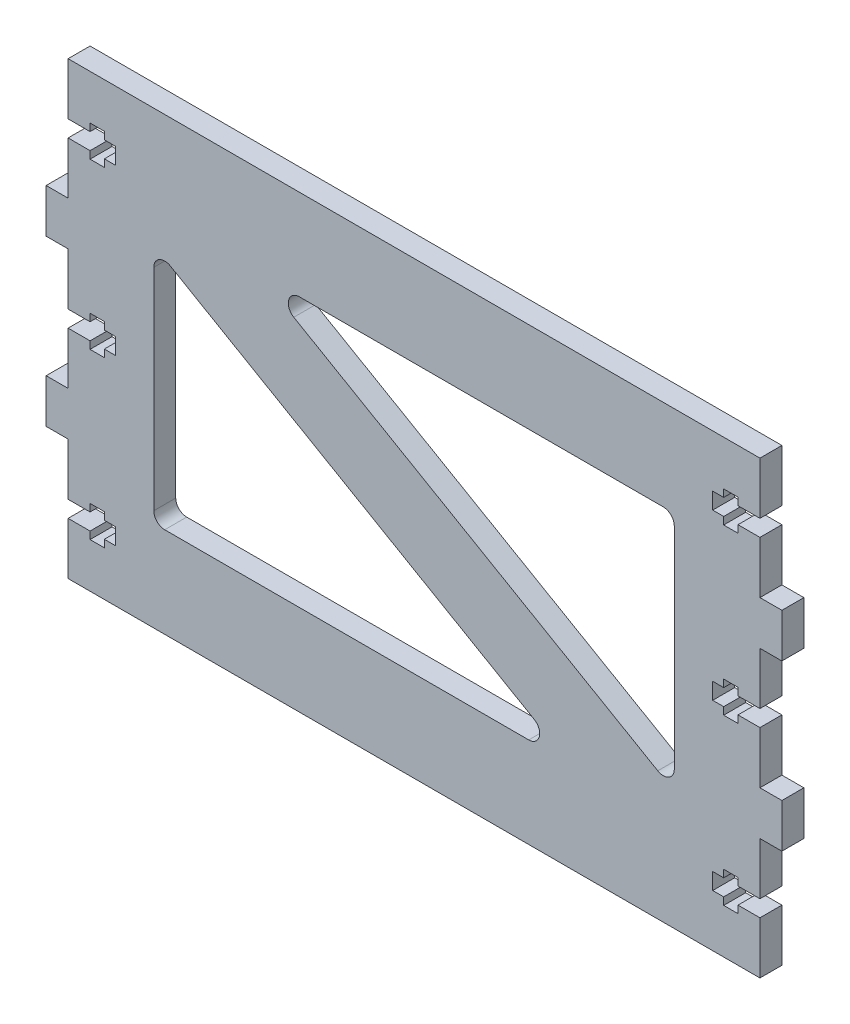
SolidWorks part; units mm, degrees
ref_plane "前视基准面" through (0, 0, 0) normal (0, 0, 1) x (1, 0, 0)
ref_plane "上视基准面" through (0, 0, 0) normal (0, 1, 0) x (1, 0, 0)
ref_plane "右视基准面" through (0, 0, 0) normal (1, 0, 0) x (0, 0, -1)
sketch "草图1" plane through (0, 0, 0) normal (0, 0, 1) x (1, 0, 0)
  line L0 (55.5343, 5.23) -> (-70.4657, 5.23) construction
  line L1 (59.5343, 20.23) -> (57.8313, 20.23) construction
  line L2 (46.9343, -24.77) -> (49.8557, -24.77) construction
  line L3 (59.5343, -9.77) -> (57.8313, -9.77) construction
  line L4 (55.5343, 3.73) -> (55.5343, 6.73) construction
  line L5 (55.5343, 5.23) -> (56.8421, 5.23) construction
  line L6 (55.5343, 6.73) -> (51.5343, 6.73)
  line L7 (51.5343, 6.73) -> (51.5343, 8.08)
  line L8 (51.5343, 8.08) -> (48.9343, 8.08)
  line L9 (48.9343, 8.08) -> (48.9343, 6.73)
  line L10 (48.9343, 6.73) -> (46.9343, 6.73)
  line L11 (48.9343, 2.38) -> (48.9343, 3.73)
  line L12 (51.5343, 3.73) -> (51.5343, 2.38)
  line L13 (48.9343, 3.73) -> (46.9343, 3.73)
  line L14 (51.5343, 2.38) -> (48.9343, 2.38)
  line L15 (55.5343, 3.73) -> (51.5343, 3.73)
  line L16 (55.5343, 24.23) -> (59.5343, 24.23)
  line L17 (59.5343, 24.23) -> (59.5343, 16.23)
  line L18 (59.5343, 16.23) -> (55.5343, 16.23)
  line L19 (55.5343, 16.23) -> (55.5343, 6.73)
  line L20 (-7.4657, 5.23) -> (-7.4657, 11.8034) construction
  line L21 (55.5343, 6.73) -> (51.5343, 6.73)
  line L22 (51.5343, 8.08) -> (48.9343, 8.08)
  line L23 (55.5343, 6.73) -> (51.5343, 6.73)
  line L24 (51.5343, 6.73) -> (51.5343, 8.08)
  line L25 (51.5343, 8.08) -> (48.9343, 8.08)
  line L26 (48.9343, 8.08) -> (48.9343, 6.73)
  line L27 (48.9343, 6.73) -> (46.9343, 6.73)
  line L28 (48.9343, 2.38) -> (48.9343, 3.73)
  line L29 (51.5343, 3.73) -> (51.5343, 2.38)
  line L30 (48.9343, 3.73) -> (46.9343, 3.73)
  line L31 (51.5343, 2.38) -> (48.9343, 2.38)
  line L32 (55.5343, 3.73) -> (51.5343, 3.73)
  line L33 (48.9343, 6.73) -> (46.9343, 6.73)
  line L34 (51.5343, 6.73) -> (51.5343, 8.08)
  line L35 (48.9343, 8.08) -> (48.9343, 6.73)
  line L36 (48.9343, 3.73) -> (46.9343, 3.73)
  line L37 (48.9343, 2.38) -> (48.9343, 3.73)
  line L38 (51.5343, 2.38) -> (48.9343, 2.38)
  line L39 (51.5343, 3.73) -> (51.5343, 2.38)
  line L40 (55.5343, 3.73) -> (51.5343, 3.73)
  line L41 (55.5343, -23.27) -> (55.5343, -13.77)
  line L42 (51.5343, -23.27) -> (55.5343, -23.27)
  line L43 (51.5343, -26.27) -> (55.5343, -26.27)
  line L44 (55.5343, -35.77) -> (55.5343, -26.27)
  line L45 (51.5343, -23.27) -> (51.5343, -21.92)
  line L46 (51.5343, -21.92) -> (48.9343, -21.92)
  line L47 (48.9343, -21.92) -> (48.9343, -23.27)
  line L48 (48.9343, -23.27) -> (46.9343, -23.27)
  line L49 (46.9343, -23.27) -> (46.9343, -26.27)
  line L50 (48.9343, -27.62) -> (48.9343, -26.27)
  line L51 (51.5343, -26.27) -> (51.5343, -27.62)
  line L52 (48.9343, -26.27) -> (46.9343, -26.27)
  line L53 (51.5343, -27.62) -> (48.9343, -27.62)
  line L54 (55.5343, -5.77) -> (55.5343, 3.73)
  line L55 (59.5343, -5.77) -> (55.5343, -5.77)
  line L56 (59.5343, -13.77) -> (59.5343, -5.77)
  line L57 (55.5343, -13.77) -> (59.5343, -13.77)
  line L58 (55.5343, 6.73) -> (51.5343, 6.73)
  line L59 (51.5343, 8.08) -> (48.9343, 8.08)
  line L60 (48.9343, 6.73) -> (46.9343, 6.73)
  line L61 (51.5343, 6.73) -> (51.5343, 8.08)
  line L62 (48.9343, 8.08) -> (48.9343, 6.73)
  line L63 (46.9343, 3.73) -> (46.9343, 6.73)
  line L64 (48.9343, 3.73) -> (46.9343, 3.73)
  line L65 (48.9343, 2.38) -> (48.9343, 3.73)
  line L66 (51.5343, 2.38) -> (48.9343, 2.38)
  line L67 (51.5343, 3.73) -> (51.5343, 2.38)
  line L68 (55.5343, 3.73) -> (51.5343, 3.73)
  line L69 (46.9343, 35.23) -> (49.8557, 35.23) construction
  line L70 (51.5343, 38.08) -> (48.9343, 38.08)
  line L71 (48.9343, 36.73) -> (46.9343, 36.73)
  line L72 (51.5343, 36.73) -> (51.5343, 38.08)
  line L73 (48.9343, 38.08) -> (48.9343, 36.73)
  line L74 (46.9343, 33.73) -> (46.9343, 36.73)
  line L75 (48.9343, 33.73) -> (46.9343, 33.73)
  line L76 (48.9343, 32.38) -> (48.9343, 33.73)
  line L77 (51.5343, 32.38) -> (48.9343, 32.38)
  line L78 (51.5343, 33.73) -> (51.5343, 32.38)
  line L79 (55.5343, 46.23) -> (55.5343, 36.73)
  line L80 (51.5343, 36.73) -> (55.5343, 36.73)
  line L81 (51.5343, 33.73) -> (55.5343, 33.73)
  line L82 (55.5343, 33.73) -> (55.5343, 24.23)
  line L83 (-61.8657, 35.23) -> (-64.7872, 35.23) construction
  line L84 (-70.4657, 5.23) -> (-71.7735, 5.23) construction
  line L85 (-70.4657, 3.73) -> (-70.4657, 6.73) construction
  line L86 (-74.4657, -9.77) -> (-72.7628, -9.77) construction
  line L87 (-61.8657, -24.77) -> (-64.7872, -24.77) construction
  line L88 (-74.4657, 20.23) -> (-72.7628, 20.23) construction
  line L89 (-70.4657, 33.73) -> (-70.4657, 24.23)
  line L90 (-66.4657, 33.73) -> (-70.4657, 33.73)
  line L91 (-66.4657, 36.73) -> (-70.4657, 36.73)
  line L92 (-70.4657, 46.23) -> (-70.4657, 36.73)
  line L93 (-66.4657, 33.73) -> (-66.4657, 32.38)
  line L94 (-66.4657, 32.38) -> (-63.8657, 32.38)
  line L95 (-63.8657, 32.38) -> (-63.8657, 33.73)
  line L96 (-63.8657, 33.73) -> (-61.8657, 33.73)
  line L97 (-61.8657, 33.73) -> (-61.8657, 36.73)
  line L98 (-63.8657, 38.08) -> (-63.8657, 36.73)
  line L99 (-66.4657, 36.73) -> (-66.4657, 38.08)
  line L100 (-63.8657, 36.73) -> (-61.8657, 36.73)
  line L101 (-66.4657, 38.08) -> (-63.8657, 38.08)
  line L102 (-70.4657, 3.73) -> (-66.4657, 3.73)
  line L103 (-66.4657, 3.73) -> (-66.4657, 2.38)
  line L104 (-66.4657, 2.38) -> (-63.8657, 2.38)
  line L105 (-63.8657, 2.38) -> (-63.8657, 3.73)
  line L106 (-63.8657, 3.73) -> (-61.8657, 3.73)
  line L107 (-61.8657, 3.73) -> (-61.8657, 6.73)
  line L108 (-63.8657, 8.08) -> (-63.8657, 6.73)
  line L109 (-66.4657, 6.73) -> (-66.4657, 8.08)
  line L110 (-63.8657, 6.73) -> (-61.8657, 6.73)
  line L111 (-66.4657, 8.08) -> (-63.8657, 8.08)
  line L112 (-70.4657, 6.73) -> (-66.4657, 6.73)
  line L113 (-70.4657, -13.77) -> (-74.4657, -13.77)
  line L114 (-74.4657, -13.77) -> (-74.4657, -5.77)
  line L115 (-74.4657, -5.77) -> (-70.4657, -5.77)
  line L116 (-70.4657, -5.77) -> (-70.4657, 3.73)
  line L117 (-66.4657, -27.62) -> (-63.8657, -27.62)
  line L118 (-63.8657, -26.27) -> (-61.8657, -26.27)
  line L119 (-66.4657, -26.27) -> (-66.4657, -27.62)
  line L120 (-63.8657, -27.62) -> (-63.8657, -26.27)
  line L121 (-61.8657, -23.27) -> (-61.8657, -26.27)
  line L122 (-63.8657, -23.27) -> (-61.8657, -23.27)
  line L123 (-63.8657, -21.92) -> (-63.8657, -23.27)
  line L124 (-66.4657, -21.92) -> (-63.8657, -21.92)
  line L125 (-66.4657, -23.27) -> (-66.4657, -21.92)
  line L126 (-70.4657, -35.77) -> (-70.4657, -26.27)
  line L127 (-66.4657, -26.27) -> (-70.4657, -26.27)
  line L128 (-66.4657, -23.27) -> (-70.4657, -23.27)
  line L129 (-70.4657, -23.27) -> (-70.4657, -13.77)
  line L130 (-70.4657, 3.73) -> (-66.4657, 3.73)
  line L131 (-66.4657, 3.73) -> (-66.4657, 2.38)
  line L132 (-66.4657, 2.38) -> (-63.8657, 2.38)
  line L133 (-63.8657, 2.38) -> (-63.8657, 3.73)
  line L134 (-63.8657, 3.73) -> (-61.8657, 3.73)
  line L135 (-63.8657, 8.08) -> (-63.8657, 6.73)
  line L136 (-66.4657, 6.73) -> (-66.4657, 8.08)
  line L137 (-63.8657, 6.73) -> (-61.8657, 6.73)
  line L138 (-70.4657, 3.73) -> (-66.4657, 3.73)
  line L139 (-66.4657, 2.38) -> (-63.8657, 2.38)
  line L140 (-63.8657, 3.73) -> (-61.8657, 3.73)
  line L141 (-66.4657, 3.73) -> (-66.4657, 2.38)
  line L142 (-63.8657, 2.38) -> (-63.8657, 3.73)
  line L143 (-63.8657, 6.73) -> (-61.8657, 6.73)
  line L144 (-63.8657, 8.08) -> (-63.8657, 6.73)
  line L145 (-66.4657, 8.08) -> (-63.8657, 8.08)
  line L146 (-66.4657, 6.73) -> (-66.4657, 8.08)
  line L147 (-70.4657, 6.73) -> (-66.4657, 6.73)
  line L148 (-66.4657, 8.08) -> (-63.8657, 8.08)
  line L149 (-70.4657, 6.73) -> (-66.4657, 6.73)
  line L150 (-70.4657, 16.23) -> (-70.4657, 6.73)
  line L151 (-74.4657, 16.23) -> (-70.4657, 16.23)
  line L152 (-74.4657, 24.23) -> (-74.4657, 16.23)
  line L153 (-70.4657, 24.23) -> (-74.4657, 24.23)
  line L154 (-70.4657, 3.73) -> (-66.4657, 3.73)
  line L155 (-66.4657, 2.38) -> (-63.8657, 2.38)
  line L156 (-63.8657, 3.73) -> (-61.8657, 3.73)
  line L157 (-66.4657, 3.73) -> (-66.4657, 2.38)
  line L158 (-63.8657, 2.38) -> (-63.8657, 3.73)
  line L159 (-63.8657, 6.73) -> (-61.8657, 6.73)
  line L160 (-63.8657, 8.08) -> (-63.8657, 6.73)
  line L161 (-66.4657, 8.08) -> (-63.8657, 8.08)
  line L162 (-66.4657, 6.73) -> (-66.4657, 8.08)
  line L163 (-70.4657, 6.73) -> (-66.4657, 6.73)
  line L164 (-70.4657, 46.23) -> (55.5343, 46.23)
  line L165 (-70.4657, -35.77) -> (55.5343, -35.77)
  dimension "D1" = 3
  dimension "D2" = 15
  dimension "D3" = 63
extrude "凸台-拉伸1" add sketch "草图1" along normal blind 4 contours L126 L165 L44 L43 L51 L53 L50 L52 L49 L48 L47 L46 L45 L42 L41 L57 L56 L55 L54 L15 L12 L14 L11 L13 L63 L10 L9 L8 L7 L6 L19 L18 L17 L16 L82 L81 L78 L77 L76 L75 L74 L71 L73 L70 L72 L80 L79 L164 L92 L91 L99
sketch "草图2" plane through (55.5343, 0, 0) normal (1, 0, 0) x (0, 0, -1)
  line L0 (-2, -26.27) -> (-2, -23.27)
  line L1 (-4, -26.27) -> (0, -26.27) construction
  line L2 (-4, -23.27) -> (0, -23.27) construction
  circle A0 centre (-2, -24.77) radius 1.5
sketch "草图3" plane through (0, 0, 4) normal (0, 0, 1) x (1, 0, 0)
  line L1 (55.5343, -35.77) -> (55.5343, -26.27) construction
  line L2 (-70.4657, -35.77) -> (55.5343, -35.77) construction
  line L3 (55.5343, -35.77) -> (55.5343, 46.23)
  line L4 (55.5343, 46.23) -> (55.5343, 36.73) construction
  line L5 (-70.4657, 46.23) -> (55.5343, 46.23) construction
  line L10 (36.9321, -12.3894) -> (-29.3645, 25.9992)
  line L11 (-28.3623, 29.73) -> (37.9343, 29.73)
  line L12 (39.9343, 27.73) -> (39.9343, -10.6587)
  line L15 (14.4331, -15.5392) -> (-51.8635, 22.8494)
  line L18 (-54.8657, 21.1187) -> (-54.8657, -17.27)
  line L19 (-52.8657, -19.27) -> (13.4309, -19.27)
  arc A0 (39.9343, 27.73) -> (37.9343, 29.73) centre (37.9343, 27.73) ccw
  arc A1 (39.9343, -10.6587) -> (36.9321, -12.3894) centre (37.9343, -10.6587) cw
  arc A2 (-28.3623, 29.73) -> (-29.3645, 25.9992) centre (-28.3623, 27.73) ccw
  arc A3 (13.4309, -19.27) -> (14.4331, -15.5392) centre (13.4309, -17.27) ccw
  arc A4 (-52.8657, -19.27) -> (-54.8657, -17.27) centre (-52.8657, -17.27) cw
  arc A5 (-51.8635, 22.8494) -> (-54.8657, 21.1187) centre (-52.8657, 21.1187) ccw
  dimension "D1" = 2
extrude "切除-拉伸1" cut sketch "草图3" against normal blind 10 contours L15 A5 L18 A4 L19 A3 | L11 A2 L10 A1 L12 A0
